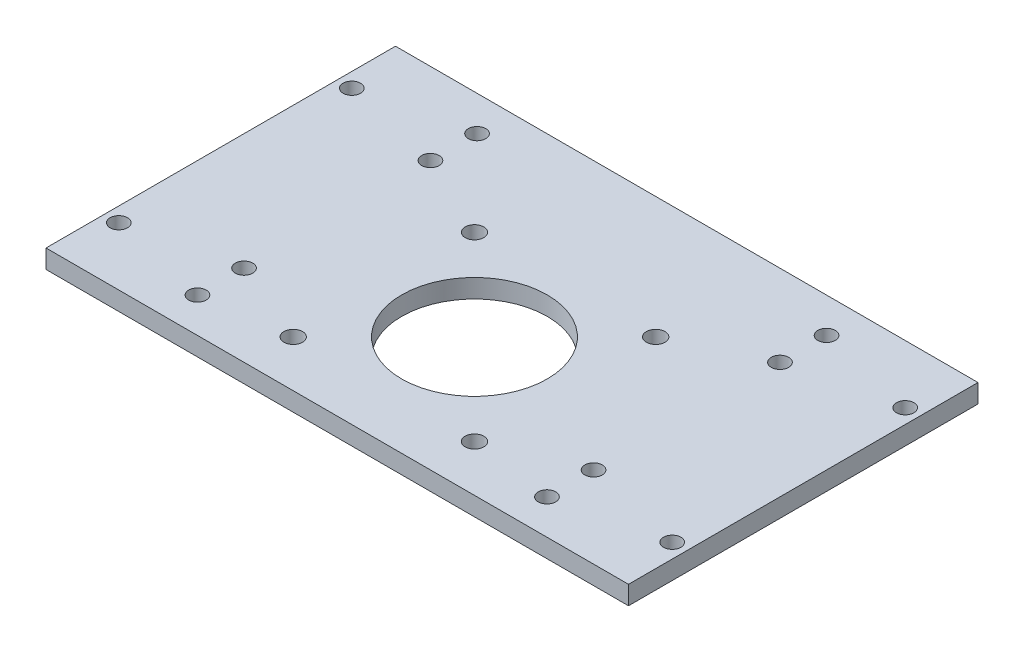
SolidWorks part; units mm, degrees
ref_plane "前视基准面" through (0, 0, 0) normal (0, 0, 1) x (1, 0, 0)
ref_plane "上视基准面" through (0, 0, 0) normal (0, 1, 0) x (1, 0, 0)
ref_plane "右视基准面" through (0, 0, 0) normal (1, 0, 0) x (0, 0, -1)
other "Configuration Table"
sketch "草图1" plane through (0, 0, 0) normal (0, 1, 0) x (1, 0, 0)
  line L0 (0, 30) -> (0, -30) construction
  line L1 (-50, 30) -> (50, 30)
  line L2 (-50, 30) -> (-50, -30)
  line L3 (-50, -30) -> (50, -30)
  line L4 (50, 30) -> (50, -30)
  line L6 (-50, 0) -> (50, 0) construction
  dimension "D1" = 60
  dimension "D2" = 100
extrude "凸台-拉伸1" add sketch "草图1" along normal blind 3.2
sketch "草图2" plane through (0, 3.2, 0) normal (0, 1, 0) x (1, 0, 0)
  line L0 (0, 0) -> (0, -30) construction
  line L1 (-50, -30) -> (50, -30) construction
  line L2 (0, 0) -> (0, 30) construction
  line L3 (50, 30) -> (-50, 30) construction
  line L4 (-15.5563, -22) -> (15.5563, -22) construction
  line L5 (0, -6.4437) -> (0, -22) construction
  line L6 (-50, 0) -> (50, 0) construction
  line L7 (-50, 30) -> (-50, -30) construction
  line L8 (50, -30) -> (50, 30) construction
  line L9 (-47.5, 30) -> (-47.5, -30) construction
  line L10 (-50, -20) -> (50, -20) construction
  line L11 (-50, 20) -> (50, 20) construction
  circle A0 centre (0, -6.4437) radius 12.5
  circle A1 centre (15.5563, -22) radius 1.6
  circle A2 centre (15.5563, 9.1127) radius 1.6
  circle A3 centre (-15.5563, 9.1127) radius 1.6
  circle A4 centre (-15.5563, -22) radius 1.6
  circle A5 centre (-47.5, 20) radius 1.5
  circle A6 centre (-47.5, -20) radius 1.5
  circle A7 centre (47.5, -20) radius 1.5
  circle A8 centre (47.5, 20) radius 1.5
  circle A9 centre (-30, -24) radius 1.5
  circle A10 centre (-30, -16) radius 1.5
  circle A11 centre (-30, 24) radius 1.5
  circle A12 centre (-30, 16) radius 1.5
  circle A13 centre (30, -24) radius 1.5
  circle A14 centre (30, -16) radius 1.5
  circle A15 centre (30, 24) radius 1.5
  circle A16 centre (30, 16) radius 1.5
  dimension "D1" = 25
  dimension "D2" = 3.2
  dimension "D6" = 3
  dimension "D7" = 3
  dimension "D12" = 3
  dimension "D3" = 22
  dimension "D5" = 8
  dimension "D8" = 20
  dimension "D9" = 20
  dimension "D10" = 2.5
  dimension "D11" = 20
  dimension "D13" = 20
  dimension "D14" = 4
  dimension "D4" = 4
extrude "切除-拉伸1" cut sketch "草图2" against normal up to surface (3.2 mm away) up to face at (0, 0, 0)
sketch "草图3" plane through (0, 3.2, 0) normal (0, 1, 0) x (1, 0, 0)
  line L0 (0, 30) -> (0, -30) construction
  line L1 (50, 30) -> (-50, 30) construction
  line L2 (-50, -30) -> (50, -30) construction
  line L3 (-50, 0) -> (50, 0) construction
  line L4 (-50, 30) -> (-50, -30) construction
  line L5 (50, -30) -> (50, 30) construction
  line L6 (-28, 26.8) -> (28, 26.8) construction
  line L7 (-28, 28.4) -> (28, 28.4)
  line L8 (-28, 25.2) -> (28, 25.2)
  line L9 (-28, 21.6) -> (28, 21.6) construction
  line L10 (-28, 23.2) -> (28, 23.2)
  line L11 (-28, 20) -> (28, 20)
  line L12 (-28, 16.4) -> (28, 16.4) construction
  line L13 (-28, 18) -> (28, 18)
  line L14 (-28, 14.8) -> (28, 14.8)
  line L15 (-8, 10.4) -> (8, 10.4) construction
  line L16 (-8, 12) -> (8, 12)
  line L17 (-8, 8.8) -> (8, 8.8)
  line L18 (-8, -24) -> (8, -24) construction
  line L19 (-8, -22.4) -> (8, -22.4)
  line L20 (-8, -25.6) -> (8, -25.6)
  line L21 (-44, 12) -> (-44, -12) construction
  line L22 (-42, 12) -> (-42, -12)
  line L23 (-46, 12) -> (-46, -12)
  line L24 (-36, 12) -> (-36, -12) construction
  line L25 (-34, 12) -> (-34, -12)
  line L26 (-38, 12) -> (-38, -12)
  line L27 (-26, 12) -> (-26, -12) construction
  line L30 (-24, 12) -> (-24, -12)
  line L31 (-28, 12) -> (-28, -12)
  line L32 (44, 12) -> (44, -12) construction
  line L35 (-16, 8) -> (-16, -8) construction
  line L36 (-14, 8) -> (-14, -8)
  line L37 (-18, 8) -> (-18, -8)
  line L38 (42, 12) -> (42, -12)
  line L39 (46, 12) -> (46, -12)
  line L40 (36, 12) -> (36, -12) construction
  line L41 (34, 12) -> (34, -12)
  line L42 (38, 12) -> (38, -12)
  line L43 (26, 12) -> (26, -12) construction
  line L44 (24, 12) -> (24, -12)
  line L45 (28, 12) -> (28, -12)
  line L46 (16, 8) -> (16, -8) construction
  line L47 (14, 8) -> (14, -8)
  line L48 (18, 8) -> (18, -8)
  line L49 (-16, 8) -> (-16, -30) construction
  line L50 (-20.5, -17.2) -> (-11.5, -17.2) construction
  line L51 (-20.5, -16) -> (-11.5, -16)
  line L52 (-20.5, -18.4) -> (-11.5, -18.4)
  line L53 (-20.5, -20.4) -> (-11.5, -20.4) construction
  line L54 (-20.5, -19.2) -> (-11.5, -19.2)
  line L55 (-20.5, -21.6) -> (-11.5, -21.6)
  line L56 (-20.5, -23.6) -> (-11.5, -23.6) construction
  line L57 (-20.5, -22.4) -> (-11.5, -22.4)
  line L58 (-20.5, -24.8) -> (-11.5, -24.8)
  line L59 (-20.5, -26.8) -> (-11.5, -26.8) construction
  line L60 (-20.5, -25.6) -> (-11.5, -25.6)
  line L61 (-20.5, -28) -> (-11.5, -28)
  line L62 (-42, -12) -> (-38, -12) construction
  line L63 (-40, -12) -> (-40, -30) construction
  line L64 (-42.5, -15.2) -> (-37.5, -15.2) construction
  line L67 (-42.5, -18.4) -> (-37.5, -18.4) construction
  line L70 (-42.5, -24.8) -> (-37.5, -24.8) construction
  line L73 (-42.5, -23.8) -> (-37.5, -23.8)
  line L76 (-42.5, -28) -> (-37.5, -28) construction
  line L77 (-42.5, -27) -> (-37.5, -27)
  line L78 (-42.5, -29) -> (-37.5, -29)
  line L79 (-42.5, -17.4) -> (-37.5, -17.4)
  line L80 (-42.5, -19.4) -> (-37.5, -19.4)
  line L81 (-20.5, -14) -> (-11.5, -14) construction
  line L82 (-20.5, -12.8) -> (-11.5, -12.8)
  line L83 (-20.5, -15.2) -> (-11.5, -15.2)
  line L84 (-42.5, -25.8) -> (-37.5, -25.8)
  line L85 (-42.5, -21.6) -> (-37.5, -21.6) construction
  line L86 (-42.5, -20.6) -> (-37.5, -20.6)
  line L87 (-42.5, -22.6) -> (-37.5, -22.6)
  line L88 (-42.5, -14.2) -> (-37.5, -14.2)
  line L89 (-42.5, -16.2) -> (-37.5, -16.2)
  line L90 (42.5, -15.2) -> (37.5, -15.2) construction
  line L91 (42.5, -14.2) -> (37.5, -14.2)
  line L92 (42.5, -16.2) -> (37.5, -16.2)
  line L93 (42.5, -18.4) -> (37.5, -18.4) construction
  line L94 (42.5, -17.4) -> (37.5, -17.4)
  line L95 (42.5, -19.4) -> (37.5, -19.4)
  line L96 (42.5, -21.6) -> (37.5, -21.6) construction
  line L97 (42.5, -20.6) -> (37.5, -20.6)
  line L98 (42.5, -22.6) -> (37.5, -22.6)
  line L99 (42.5, -24.8) -> (37.5, -24.8) construction
  line L100 (42.5, -23.8) -> (37.5, -23.8)
  line L101 (42.5, -25.8) -> (37.5, -25.8)
  line L102 (42.5, -28) -> (37.5, -28) construction
  line L103 (42.5, -27) -> (37.5, -27)
  line L104 (42.5, -29) -> (37.5, -29)
  line L105 (20.5, -26.8) -> (11.5, -26.8) construction
  line L106 (20.5, -25.6) -> (11.5, -25.6)
  line L107 (20.5, -28) -> (11.5, -28)
  line L108 (20.5, -23.6) -> (11.5, -23.6) construction
  line L109 (20.5, -22.4) -> (11.5, -22.4)
  line L110 (20.5, -24.8) -> (11.5, -24.8)
  line L111 (20.5, -20.4) -> (11.5, -20.4) construction
  line L112 (20.5, -19.2) -> (11.5, -19.2)
  line L113 (20.5, -21.6) -> (11.5, -21.6)
  line L114 (20.5, -17.2) -> (11.5, -17.2) construction
  line L115 (20.5, -16) -> (11.5, -16)
  line L116 (20.5, -18.4) -> (11.5, -18.4)
  line L117 (20.5, -14) -> (11.5, -14) construction
  line L118 (20.5, -12.8) -> (11.5, -12.8)
  line L119 (20.5, -15.2) -> (11.5, -15.2)
  line L120 (-42.5, 15.2) -> (-37.5, 15.2) construction
  line L121 (-42.5, 14.2) -> (-37.5, 14.2)
  line L122 (-42.5, 16.2) -> (-37.5, 16.2)
  line L123 (-42.5, 18.4) -> (-37.5, 18.4) construction
  line L124 (-42.5, 17.4) -> (-37.5, 17.4)
  line L125 (-42.5, 19.4) -> (-37.5, 19.4)
  line L126 (-42.5, 21.6) -> (-37.5, 21.6) construction
  line L127 (-42.5, 20.6) -> (-37.5, 20.6)
  line L128 (-42.5, 22.6) -> (-37.5, 22.6)
  line L129 (-42.5, 24.8) -> (-37.5, 24.8) construction
  line L130 (-42.5, 23.8) -> (-37.5, 23.8)
  line L131 (-42.5, 25.8) -> (-37.5, 25.8)
  line L132 (-42.5, 28) -> (-37.5, 28) construction
  line L133 (-42.5, 27) -> (-37.5, 27)
  line L134 (-42.5, 29) -> (-37.5, 29)
  line L135 (42.5, 15.2) -> (37.5, 15.2) construction
  line L136 (42.5, 14.2) -> (37.5, 14.2)
  line L137 (42.5, 16.2) -> (37.5, 16.2)
  line L138 (42.5, 18.4) -> (37.5, 18.4) construction
  line L139 (42.5, 17.4) -> (37.5, 17.4)
  line L140 (42.5, 19.4) -> (37.5, 19.4)
  line L141 (42.5, 21.6) -> (37.5, 21.6) construction
  line L142 (42.5, 20.6) -> (37.5, 20.6)
  line L143 (42.5, 22.6) -> (37.5, 22.6)
  line L144 (42.5, 24.8) -> (37.5, 24.8) construction
  line L145 (42.5, 23.8) -> (37.5, 23.8)
  line L146 (42.5, 25.8) -> (37.5, 25.8)
  line L147 (42.5, 28) -> (37.5, 28) construction
  line L148 (42.5, 27) -> (37.5, 27)
  line L149 (42.5, 29) -> (37.5, 29)
  arc A0 (-28, 28.4) -> (-28, 25.2) centre (-28, 26.8) ccw
  arc A1 (28, 25.2) -> (28, 28.4) centre (28, 26.8) ccw
  arc A2 (-28, 23.2) -> (-28, 20) centre (-28, 21.6) ccw
  arc A3 (28, 20) -> (28, 23.2) centre (28, 21.6) ccw
  arc A4 (-28, 18) -> (-28, 14.8) centre (-28, 16.4) ccw
  arc A5 (28, 14.8) -> (28, 18) centre (28, 16.4) ccw
  arc A6 (-8, 12) -> (-8, 8.8) centre (-8, 10.4) ccw
  arc A7 (8, 8.8) -> (8, 12) centre (8, 10.4) ccw
  arc A8 (-8, -22.4) -> (-8, -25.6) centre (-8, -24) ccw
  arc A9 (8, -25.6) -> (8, -22.4) centre (8, -24) ccw
  arc A10 (-42, 12) -> (-46, 12) centre (-44, 12) ccw
  arc A11 (-46, -12) -> (-42, -12) centre (-44, -12) ccw
  arc A12 (-34, 12) -> (-38, 12) centre (-36, 12) ccw
  arc A13 (-38, -12) -> (-34, -12) centre (-36, -12) ccw
  arc A16 (-24, 12) -> (-28, 12) centre (-26, 12) ccw
  arc A17 (-28, -12) -> (-24, -12) centre (-26, -12) ccw
  arc A20 (-14, 8) -> (-18, 8) centre (-16, 8) ccw
  arc A21 (-18, -8) -> (-14, -8) centre (-16, -8) ccw
  arc A22 (42, 12) -> (46, 12) centre (44, 12) cw
  arc A23 (46, -12) -> (42, -12) centre (44, -12) cw
  arc A24 (34, 12) -> (38, 12) centre (36, 12) cw
  arc A25 (38, -12) -> (34, -12) centre (36, -12) cw
  arc A26 (24, 12) -> (28, 12) centre (26, 12) cw
  arc A27 (28, -12) -> (24, -12) centre (26, -12) cw
  arc A28 (14, 8) -> (18, 8) centre (16, 8) cw
  arc A29 (18, -8) -> (14, -8) centre (16, -8) cw
  arc A30 (-20.5, -16) -> (-20.5, -18.4) centre (-20.5, -17.2) ccw
  arc A31 (-11.5, -18.4) -> (-11.5, -16) centre (-11.5, -17.2) ccw
  arc A32 (-20.5, -19.2) -> (-20.5, -21.6) centre (-20.5, -20.4) ccw
  arc A33 (-11.5, -21.6) -> (-11.5, -19.2) centre (-11.5, -20.4) ccw
  arc A34 (-20.5, -22.4) -> (-20.5, -24.8) centre (-20.5, -23.6) ccw
  arc A35 (-11.5, -24.8) -> (-11.5, -22.4) centre (-11.5, -23.6) ccw
  arc A36 (-20.5, -25.6) -> (-20.5, -28) centre (-20.5, -26.8) ccw
  arc A37 (-11.5, -28) -> (-11.5, -25.6) centre (-11.5, -26.8) ccw
  arc A46 (-42.5, -27) -> (-42.5, -29) centre (-42.5, -28) ccw
  arc A47 (-37.5, -29) -> (-37.5, -27) centre (-37.5, -28) ccw
  arc A48 (-42.5, -17.4) -> (-42.5, -19.4) centre (-42.5, -18.4) ccw
  arc A49 (-37.5, -19.4) -> (-37.5, -17.4) centre (-37.5, -18.4) ccw
  arc A50 (-20.5, -12.8) -> (-20.5, -15.2) centre (-20.5, -14) ccw
  arc A51 (-11.5, -15.2) -> (-11.5, -12.8) centre (-11.5, -14) ccw
  arc A52 (-42.5, -23.8) -> (-42.5, -25.8) centre (-42.5, -24.8) ccw
  arc A53 (-37.5, -25.8) -> (-37.5, -23.8) centre (-37.5, -24.8) ccw
  arc A54 (-42.5, -20.6) -> (-42.5, -22.6) centre (-42.5, -21.6) ccw
  arc A55 (-37.5, -22.6) -> (-37.5, -20.6) centre (-37.5, -21.6) ccw
  arc A56 (-42.5, -14.2) -> (-42.5, -16.2) centre (-42.5, -15.2) ccw
  arc A57 (-37.5, -16.2) -> (-37.5, -14.2) centre (-37.5, -15.2) ccw
  arc A58 (42.5, -14.2) -> (42.5, -16.2) centre (42.5, -15.2) cw
  arc A59 (37.5, -16.2) -> (37.5, -14.2) centre (37.5, -15.2) cw
  arc A60 (42.5, -17.4) -> (42.5, -19.4) centre (42.5, -18.4) cw
  arc A61 (37.5, -19.4) -> (37.5, -17.4) centre (37.5, -18.4) cw
  arc A62 (42.5, -20.6) -> (42.5, -22.6) centre (42.5, -21.6) cw
  arc A63 (37.5, -22.6) -> (37.5, -20.6) centre (37.5, -21.6) cw
  arc A64 (42.5, -23.8) -> (42.5, -25.8) centre (42.5, -24.8) cw
  arc A65 (37.5, -25.8) -> (37.5, -23.8) centre (37.5, -24.8) cw
  arc A66 (42.5, -27) -> (42.5, -29) centre (42.5, -28) cw
  arc A67 (37.5, -29) -> (37.5, -27) centre (37.5, -28) cw
  arc A68 (20.5, -25.6) -> (20.5, -28) centre (20.5, -26.8) cw
  arc A69 (11.5, -28) -> (11.5, -25.6) centre (11.5, -26.8) cw
  arc A70 (20.5, -22.4) -> (20.5, -24.8) centre (20.5, -23.6) cw
  arc A71 (11.5, -24.8) -> (11.5, -22.4) centre (11.5, -23.6) cw
  arc A72 (20.5, -19.2) -> (20.5, -21.6) centre (20.5, -20.4) cw
  arc A73 (11.5, -21.6) -> (11.5, -19.2) centre (11.5, -20.4) cw
  arc A74 (20.5, -16) -> (20.5, -18.4) centre (20.5, -17.2) cw
  arc A75 (11.5, -18.4) -> (11.5, -16) centre (11.5, -17.2) cw
  arc A76 (20.5, -12.8) -> (20.5, -15.2) centre (20.5, -14) cw
  arc A77 (11.5, -15.2) -> (11.5, -12.8) centre (11.5, -14) cw
  arc A78 (-42.5, 14.2) -> (-42.5, 16.2) centre (-42.5, 15.2) cw
  arc A79 (-37.5, 16.2) -> (-37.5, 14.2) centre (-37.5, 15.2) cw
  arc A80 (-42.5, 17.4) -> (-42.5, 19.4) centre (-42.5, 18.4) cw
  arc A81 (-37.5, 19.4) -> (-37.5, 17.4) centre (-37.5, 18.4) cw
  arc A82 (-42.5, 20.6) -> (-42.5, 22.6) centre (-42.5, 21.6) cw
  arc A83 (-37.5, 22.6) -> (-37.5, 20.6) centre (-37.5, 21.6) cw
  arc A84 (-42.5, 23.8) -> (-42.5, 25.8) centre (-42.5, 24.8) cw
  arc A85 (-37.5, 25.8) -> (-37.5, 23.8) centre (-37.5, 24.8) cw
  arc A86 (-42.5, 27) -> (-42.5, 29) centre (-42.5, 28) cw
  arc A87 (-37.5, 29) -> (-37.5, 27) centre (-37.5, 28) cw
  arc A88 (42.5, 14.2) -> (42.5, 16.2) centre (42.5, 15.2) ccw
  arc A89 (37.5, 16.2) -> (37.5, 14.2) centre (37.5, 15.2) ccw
  arc A90 (42.5, 17.4) -> (42.5, 19.4) centre (42.5, 18.4) ccw
  arc A91 (37.5, 19.4) -> (37.5, 17.4) centre (37.5, 18.4) ccw
  arc A92 (42.5, 20.6) -> (42.5, 22.6) centre (42.5, 21.6) ccw
  arc A93 (37.5, 22.6) -> (37.5, 20.6) centre (37.5, 21.6) ccw
  arc A94 (42.5, 23.8) -> (42.5, 25.8) centre (42.5, 24.8) ccw
  arc A95 (37.5, 25.8) -> (37.5, 23.8) centre (37.5, 24.8) ccw
  arc A96 (42.5, 27) -> (42.5, 29) centre (42.5, 28) ccw
  arc A97 (37.5, 29) -> (37.5, 27) centre (37.5, 28) ccw
  point P14 (0, 26.8)
  point P20 (0, 21.6)
  point P27 (0, 16.4)
  point P34 (0, 10.4)
  point P41 (0, -24)
  point P49 (-44, 0)
  point P56 (-36, 0)
  point P63 (-26, 0)
  point P70 (44, 0)
  point P76 (-16, 0)
  point P84 (36, 0)
  point P91 (26, 0)
  point P98 (16, 0)
  point P107 (-16, -17.2)
  point P113 (-16, -20.4)
  point P120 (-16, -23.6)
  point P127 (-16, -26.8)
  point P139 (-40, -15.2)
  point P146 (-40, -18.4)
  point P153 (-40, -24.8)
  point P160 (-40, -21.6)
  point P166 (-40, -28)
  point P175 (-16, -14)
  point P185 (40, -15.2)
  point P192 (40, -18.4)
  point P199 (40, -21.6)
  point P206 (40, -24.8)
  point P213 (40, -28)
  point P220 (16, -26.8)
  point P227 (16, -23.6)
  point P234 (16, -20.4)
  point P241 (16, -17.2)
  point P248 (16, -14)
  point P255 (-40, 15.2)
  point P262 (-40, 18.4)
  point P269 (-40, 21.6)
  point P276 (-40, 24.8)
  point P283 (-40, 28)
  point P290 (40, 15.2)
  point P297 (40, 18.4)
  point P304 (40, 21.6)
  point P311 (40, 24.8)
  point P318 (40, 28)
  dimension "D53" = 2
  dimension "D57" = 5
  dimension "D1" = 56
  dimension "D2" = 1.6
  dimension "D3" = 1.6
  dimension "D4" = 56
  dimension "D5" = 1.6
  dimension "D6" = 56
  dimension "D7" = 16
  dimension "D8" = 1.6
  dimension "D9" = 16
  dimension "D10" = 1.6
  dimension "D11" = 3.2
  dimension "D12" = 5.2
  dimension "D13" = 5.2
  dimension "D14" = 6
  dimension "D15" = 6
  dimension "D16" = 24
  dimension "D17" = 24
  dimension "D18" = 24
  dimension "D19" = 2
  dimension "D20" = 2
  dimension "D21" = 2
  dimension "D22" = 16
  dimension "D23" = 2
  dimension "D24" = 6
  dimension "D25" = 8
  dimension "D26" = 10
  dimension "D27" = 10
  dimension "D28" = 1
  dimension "D29" = 1
  dimension "D30" = 1
  dimension "D31" = 5
  dimension "D32" = 9
  dimension "D33" = 9
  dimension "D34" = 9
  dimension "D35" = 9
  dimension "D36" = 3.2
  dimension "D37" = 1.2
  dimension "D38" = 1.2
  dimension "D39" = 1.2
  dimension "D40" = 1.2
  dimension "D41" = 3.2
  dimension "D42" = 3.2
  dimension "D43" = 3.2
  dimension "D44" = 1
  dimension "D45" = 5
  dimension "D46" = 3.2
  dimension "D47" = 3.2
  dimension "D48" = 1
  dimension "D49" = 5
  dimension "D50" = 1.2
  dimension "D51" = 9
  dimension "D52" = 3.2
  dimension "D54" = 3.2
  dimension "D55" = 3.2
  dimension "D56" = 5
